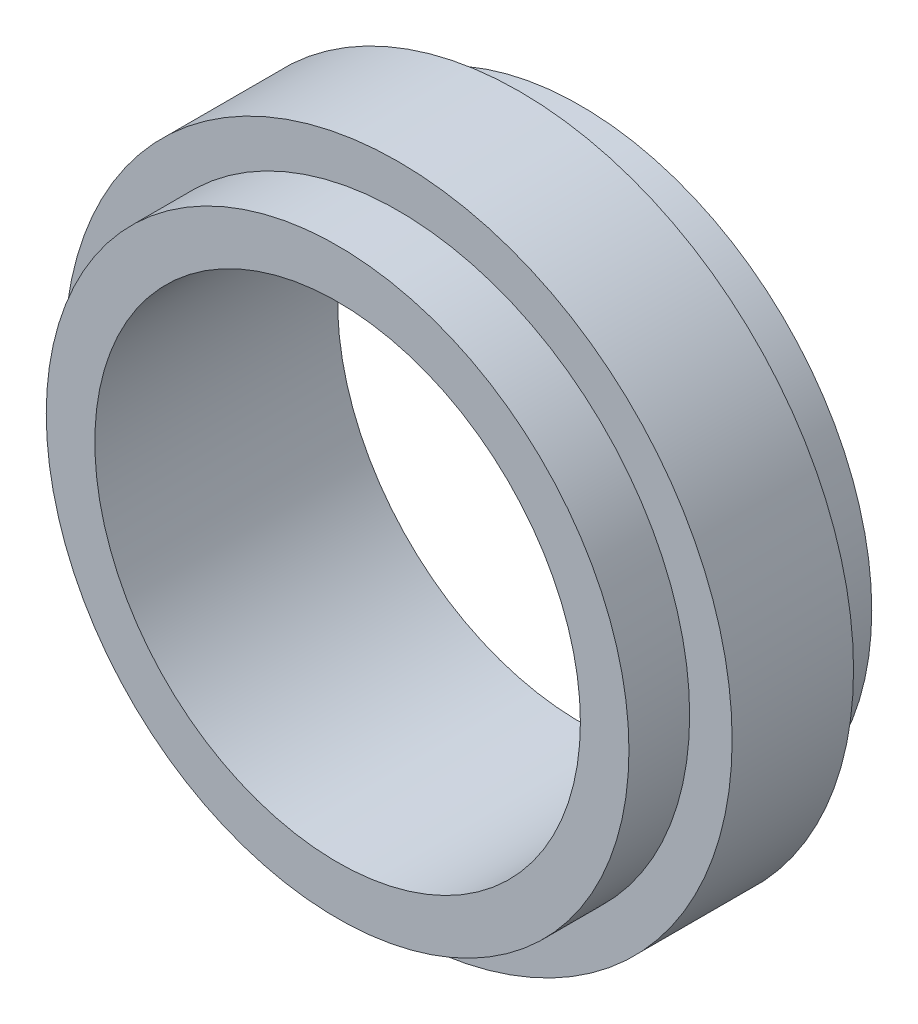
SolidWorks part; units mm, degrees
ref_plane "Ön Düzlem" through (0, 0, 0) normal (0, 0, 1) x (1, 0, 0)
ref_plane "Üst Düzlem" through (0, 0, 0) normal (0, 1, 0) x (1, 0, 0)
ref_plane "Sağ Düzlem" through (0, 0, 0) normal (1, 0, 0) x (0, 0, -1)
sketch "Sketch1" plane through (0, 0, 0) normal (0, 0, 1) x (1, 0, 0)
  circle A0 centre (0, 0) radius 27.5
  circle A1 centre (0, 0) radius 20
  dimension "D1" = 40
  dimension "D2" = 55
extrude "Boss-Extrude1" add sketch "Sketch1" along normal mid plane 10
sketch "Sketch2" plane through (0, 0, 5) normal (0, 0, 1) x (1, 0, 0)
  circle A0 centre (0, 0) radius 20 construction
  circle A1 centre (0, 0) radius 20
  circle A2 centre (0, 0) radius 24
  dimension "D1" = 48
extrude "Boss-Extrude2" add sketch "Sketch2" along normal blind 5
mirror "Mirror1" about plane through (0, 0, 0) normal (0, 0, 1) of "Boss-Extrude2"
